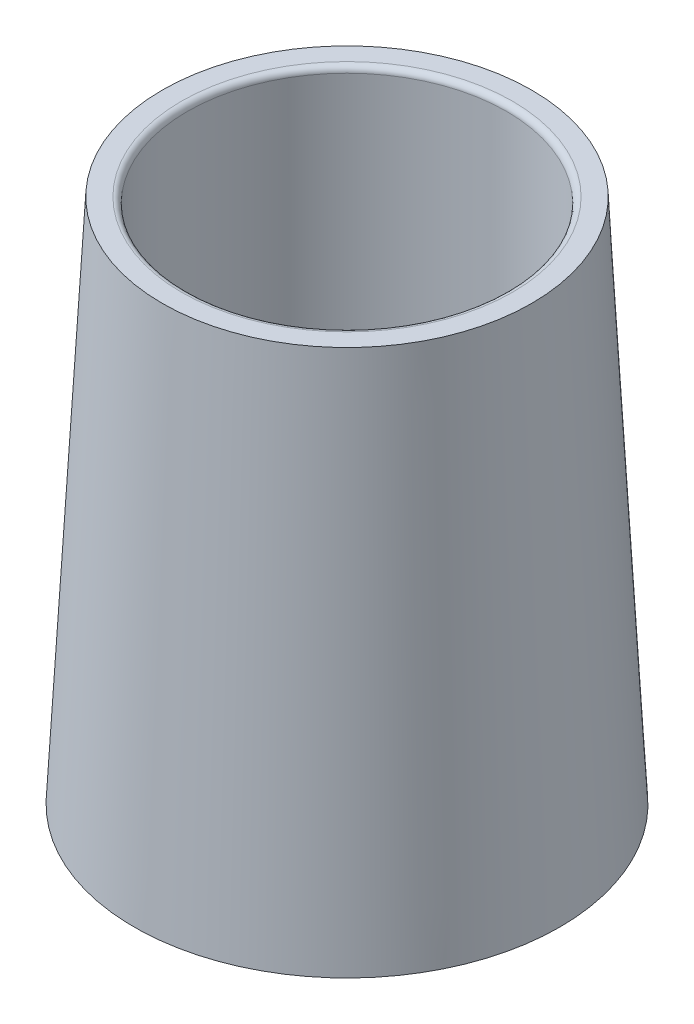
SolidWorks part; units mm, degrees
ref_plane "前基準面" through (0, 0, 0) normal (0, 0, 1) x (1, 0, 0)
ref_plane "上基準面" through (0, 0, 0) normal (0, 1, 0) x (1, 0, 0)
ref_plane "右基準面" through (0, 0, 0) normal (1, 0, 0) x (0, 0, -1)
sketch "草圖1" plane through (0, 0, 0) normal (0, 0, 1) x (1, 0, 0)
  line L0 (0, 0) -> (36, 0)
  line L1 (36, 0) -> (31.25, 89)
  line L2 (31.25, 89) -> (0, 89)
  line L3 (0, 89) -> (0, 0)
  dimension "D1" = 31.25
  dimension "D2" = 36
  dimension "D3" = 89
revolve "旋轉1" add sketch "草圖1" angle 360 about L3
sketch "草圖2" plane through (0, 89, 0) normal (0, 1, 0) x (1, 0, 0)
  circle A0 centre (0, 0) radius 27
  dimension "D1" = 54
extrude "除料-伸長1" cut sketch "草圖2" against normal blind 66
sketch "草圖3" plane through (0, 0, 0) normal (0, -1, 0) x (1, 0, 0)
  circle A0 centre (0, 0) radius 28.9
  dimension "D1" = 57.8
extrude "除料-伸長2" cut sketch "草圖3" against normal blind 11
sketch "草圖4" plane through (0, 11, 0) normal (0, -1, 0) x (1, 0, 0)
  circle A0 centre (0, 0) radius 23
  dimension "D1" = 46
extrude "除料-伸長3" cut sketch "草圖4" against normal through all
ref_plane "平面1" through (0, 0, 49.8) normal (0, 0, 1) x (1, 0, 0)
fillet "圓角1" radius 1 1 edges at (-27, 89, 0)
fillet "圓角3" radius 1 2 edges at (-23, 23, 0) (23, 11, 0)
